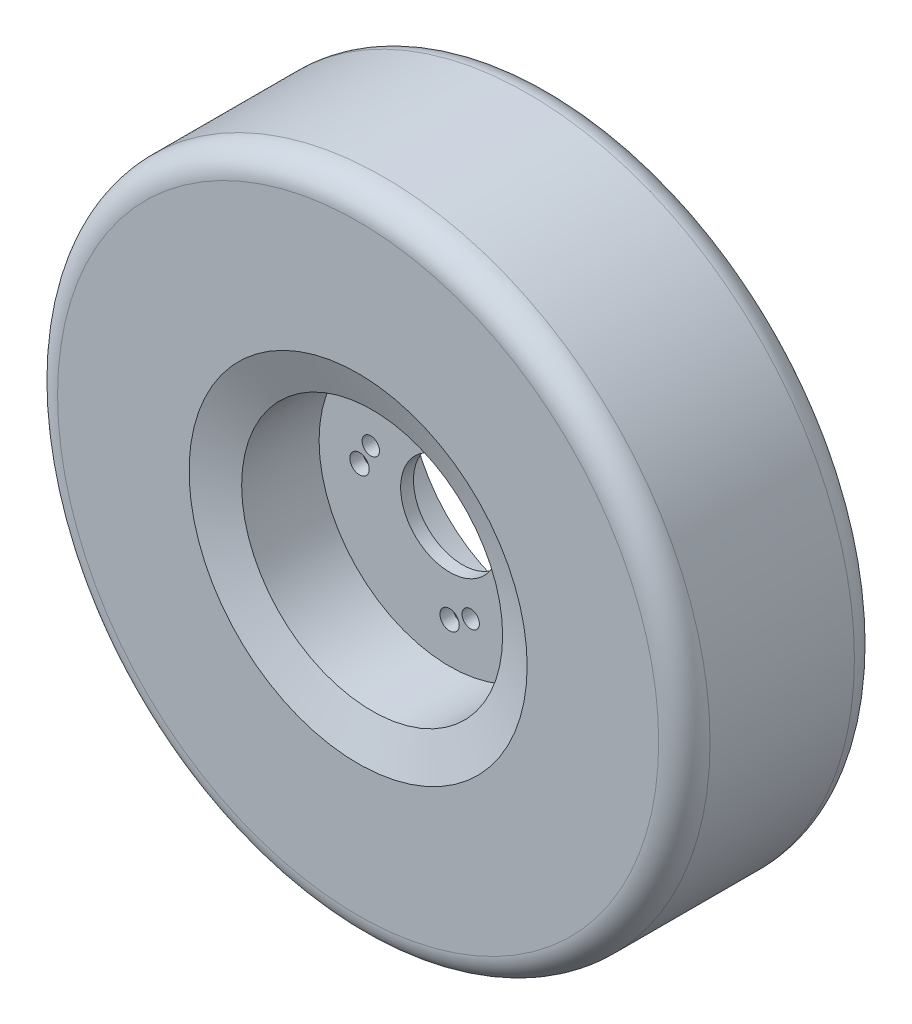
SolidWorks part; units mm, degrees
material "BUTYL"
ref_plane "Front Plane" through (0, 0, 0) normal (0, 0, 1) x (1, 0, 0)
ref_plane "Top Plane" through (0, 0, 0) normal (0, 1, 0) x (1, 0, 0)
ref_plane "Right Plane" through (0, 0, 0) normal (1, 0, 0) x (0, 0, -1)
sketch "Sketch1" plane through (0, 0, 0) normal (0, 0, 1) x (1, 0, 0)
  circle A0 centre (0, 0) radius 50.8
  circle A1 centre (0, 0) radius 127
  dimension "D1" = 254
  dimension "D2" = 101.6
extrude "Boss-Extrude1" add sketch "Sketch1" along normal mid plane 76.2
chamfer "Chamfer1" distance 15 angle 20 2 edges at (50.8, 0, 38.1) (50.8, 0, -38.1)
fillet "Fillet1" radius 10 2 edges at (127, 0, -38.1) (127, 0, 38.1)
sketch "Sketch2" plane through (0, 0, 0) normal (0, 0, 1) x (1, 0, 0)
  circle A0 centre (0, 0) radius 50.8
  circle A1 centre (0, 0) radius 50.8 construction
  circle A2 centre (0, 0) radius 19.05
  dimension "D1" = 38.1
extrude "Boss-Extrude2" add sketch "Sketch2" along normal mid plane 5
hole_wizard "19/64 (0.29688) Diameter Hole1" positions "Sketch3" profile "Sketch4" hole size "19/64" standard "ANSI Inch"
sketch "Sketch3" plane through (0, 0, 2.5) normal (0, 0, 1) x (1, 0, 0)
  line L0 (0, -35.052) -> (0, 0) construction
  line L1 (0, 0) -> (35.052, 0) construction
  line L3 (0, 35.052) -> (0, 0) construction
  line L4 (0, 0) -> (-35.052, 0) construction
  circle A0 centre (0, 0) radius 35.052 construction
  point P0 (0, 35.052)
  point P2 (35.052, 0)
  point P4 (0, -35.052)
  point P6 (-35.052, 0)
  dimension "D1" = 70.104
sketch "Sketch4" plane through (0, 35.052, 2.5) normal (1, 0, 0) x (0, -1, 0)
  line L0 (0, 0) -> (0, 21.0155)
  line L1 (0, 21.0155) -> (3.7704, 18.75)
  line L2 (3.7704, 18.75) -> (3.7704, 0)
  line L5 (3.7704, 0) -> (0, 0)
  line L10 (0, 21.0155) -> (-3.7704, 18.75) construction
  line L11 (0, -6.35) -> (0, 107.95) construction
  dimension "Hole Dia." = 7.5408
  dimension "Hole Depth" = 18.75
  dimension "Drill Angle" = 118
hole_wizard "1/4 Clearance Hole1" positions "Sketch7" profile "Sketch8" hole size "1/4" standard "ANSI Inch"
sketch "Sketch7" plane through (0, 0, 2.5) normal (0, 0, 1) x (1, 0, 0)
  line L0 (-30.6681, 8.2175) -> (0, 0) construction
  line L1 (0, 0) -> (8.2175, -30.6681) construction
  line L4 (0, 0) -> (22.4506, 22.4506) construction
  line L6 (-35.052, 0) -> (35.052, 0) construction
  line L8 (0, 0) -> (-22.4506, -22.4506) construction
  circle A0 centre (0, 0) radius 31.75 construction
  point P0 (-30.6681, 8.2175)
  point P2 (22.4506, 22.4506)
  point P4 (8.2175, -30.6681)
  dimension "D3" = 63.5
  dimension "D1" = 120
  dimension "D2" = 120
  dimension "D4" = 45
  dimension "D5" = 60
sketch "Sketch8" plane through (-30.6681, 8.2175, 2.5) normal (1, 0, 0) x (0, -1, 0)
  line L0 (0, 0) -> (0, 20.7798)
  line L1 (0, 20.7798) -> (3.3782, 18.75)
  line L2 (3.3782, 18.75) -> (3.3782, 0)
  line L5 (3.3782, 0) -> (0, 0)
  line L10 (0, 20.7798) -> (-3.3782, 18.75) construction
  line L11 (0, -6.35) -> (0, 107.95) construction
  dimension "Hole Dia." = 6.7564
  dimension "Hole Depth" = 18.75
  dimension "Drill Angle" = 118
